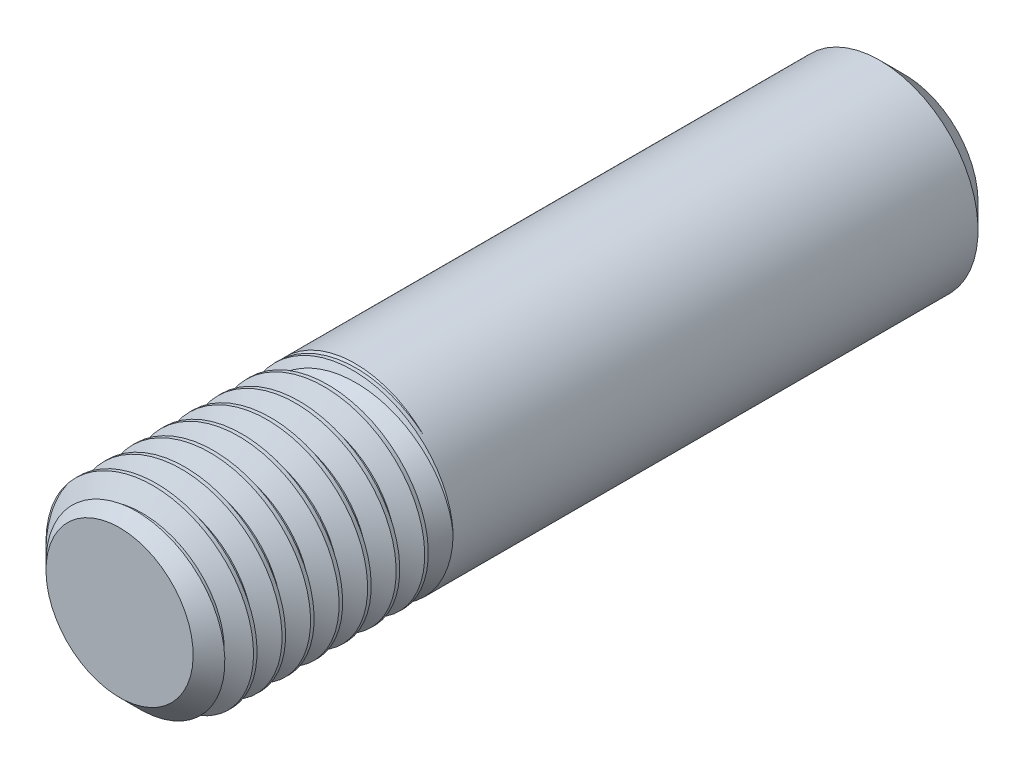
SolidWorks part; units mm, degrees
ref_plane "Front Plane" through (0, 0, 0) normal (0, 0, 1) x (1, 0, 0)
ref_plane "Top Plane" through (0, 0, 0) normal (0, 1, 0) x (1, 0, 0)
ref_plane "Right Plane" through (0, 0, 0) normal (1, 0, 0) x (0, 0, -1)
sketch "Sketch1" plane through (0, 0, 0) normal (1, 0, 0) x (0, 0, -1)
  line L0 (-31.75, 0) -> (31.75, 0) construction
  line L1 (31.75, 7.9375) -> (31.75, -7.9375) construction
  line L2 (-31.75, 7.9375) -> (-31.75, -7.9375) construction
  line L3 (-12.7, 7.9375) -> (-12.7, -7.9375) construction
  line L4 (-31.75, 7.9375) -> (-29.4409, 7.9375) construction
  line L5 (-31.75, -7.9375) -> (-25.9773, -7.9375) construction
  point P4 (31.75, 0)
  point P7 (-31.75, 0)
  point P8 (0, 0)
  point P11 (-12.7, 0)
  point P13 (-12.7, 0)
  point P17 (-25.9773, -7.9375)
  dimension "Length" = 63.5
  dimension "Thread Dia" = 15.875
  dimension "Shaft Dia" = 15.875
  dimension "Thread Length" = 19.05
  dimension "Shaft Length" = 44.45
  dimension "Pitch" = 2.3091
  dimension "D1" = 5.7727
sketch "Sketch2" plane through (0, 0, 0) normal (0, 0, 1) x (1, 0, 0)
  line L0 (-7.9375, 0) -> (7.9375, 0) construction
  line L1 (0, 7.9375) -> (0, -7.9375) construction
  circle A0 centre (0, 0) radius 7.9375 construction
  point P9 (0, 0)
  dimension "Shaft Dia" = 15.875
sketch "Sketch3" plane through (0, 0, 0) normal (1, 0, 0) x (0, 0, -1)
  line L0 (-31.75, 0) -> (31.75, 0)
  line L1 (31.75, 0) -> (31.75, 7.9375)
  line L2 (31.75, 7.9375) -> (-31.75, 7.9375) construction
  line L3 (-31.75, 7.9375) -> (-31.75, 0)
  line L4 (-31.75, 7.9375) -> (-12.7, 7.9375)
  line L5 (-12.7, 7.9375) -> (31.75, 7.9375)
revolve "Revolve1" add sketch "Sketch3" angle 360 about L0
chamfer "Chamfer1" distance 1.9844 angle 45 1 edges at (0, -7.9375, 31.75)
chamfer "Chamfer2" distance 1.9844 angle 45 1 edges at (0, -7.9375, -31.75)
ref_plane "Plane1" through (0, 0, 12.7) normal (0, 0, 1) x (1, 0, 0)
sketch "Sketch4" plane through (0, 0, 31.75) normal (0, 0, 1) x (1, 0, 0)
  circle A0 centre (0, 0) radius 7.9375
curve "Helix/Spiral1" pitch 2.3091 height 21.3591 turns 9.25
split "Split1" trim tools "Plane1" bodies to split 104 resulting bodies 105 106
sketch "Sketch5" plane through (0, 0, 0) normal (1, 0, 0) x (0, 0, -1)
  line L0 (-33.9148, 8.1875) -> (-31.6057, 8.1875) construction
  line L1 (-31.6057, 8.1875) -> (-32.7602, 6.1877) construction
  line L2 (-32.7602, 6.1877) -> (-33.9148, 8.1875) construction
  line L3 (-33.8426, 8.0625) -> (-31.6778, 8.0625) construction
  line L4 (-33.7705, 7.9375) -> (-31.75, 7.9375) construction
  line L5 (-32.9045, 6.4377) -> (-32.6159, 6.4377) construction
  line L6 (-32.7602, 6.4377) -> (-32.7602, 6.1877) construction
  line L7 (-32.7602, 7.9375) -> (-32.7602, 8.1875) construction
  line L8 (-33.8426, 8.0625) -> (-31.6778, 8.0625)
  line L9 (-31.6778, 8.0625) -> (-32.6159, 6.4377)
  line L10 (-32.6159, 6.4377) -> (-32.9045, 6.4377)
  line L11 (-32.9045, 6.4377) -> (-33.8426, 8.0625)
  point P12 (-32.7602, 8.0625)
  dimension "D1" = 2.3091
  dimension "D2" = 0.2886
sweep "Cut-Sweep1" cut profiles "Sketch5" path "Helix/Spiral1"
sketch "Sketch6" plane through (0, 0, 12.7) normal (0, 0, 1) x (1, 0, 0)
  circle A1 centre (0, 0) radius 7.9375
  circle A2 centre (0, 0) radius 7.9375
  dimension "D1" = 0
extrude "Boss-Extrude1" add sketch "Sketch6" along normal through all draft 30
equation "\"D1@Chamfer1\"=\"Thread Dia@Sketch1\"*.125"
equation "\"D1@Chamfer2\"=\"Shaft Dia@Sketch1\"*.125"
equation "\"D3@Helix/Spiral1\"=\"Thread Length@Sketch1\"+\"Pitch@Sketch1\""
equation "\"D4@Helix/Spiral1\"=\"Pitch@Sketch1\""
equation "\"D2@Sketch5\"=\"D1@Sketch5\"/8"
equation "\"D1@Sketch5\"=\"Pitch@Sketch1\""
equation "\"D1@Sketch1\"=\"Pitch@Sketch1\"*2.5"
